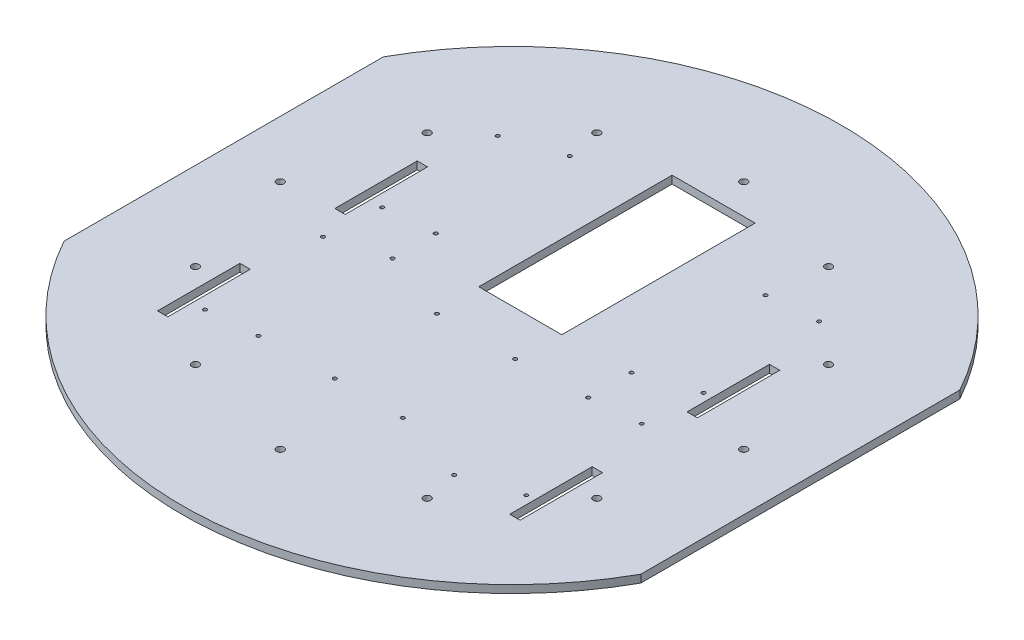
SolidWorks part; units mm, degrees
ref_plane "Front Plane" through (0, 0, 0) normal (0, 0, 1) x (1, 0, 0)
ref_plane "Top Plane" through (0, 0, 0) normal (0, 1, 0) x (1, 0, 0)
ref_plane "Right Plane" through (0, 0, 0) normal (1, 0, 0) x (0, 0, -1)
sketch "Sketch1" plane through (0, 0, 0) normal (0, 1, 0) x (1, 0, 0)
  line L0 (177.8, 98.3738) -> (177.8, -98.3738)
  line L1 (-177.8, 98.3738) -> (-177.8, -98.3738)
  line L2 (0, 0) -> (0, -203.2) construction
  arc A0 (-177.8, -98.3738) -> (177.8, -98.3738) centre (0, 0) ccw
  arc A1 (177.8, 98.3738) -> (-177.8, 98.3738) centre (0, 0) ccw
  dimension "D1" = 406.4
  dimension "D2" = 355.6
extrude "Boss-Extrude1" add sketch "Sketch1" along normal blind 4.7625
sketch "Sketch2" plane through (0, 4.7625, 0) normal (0, 1, 0) x (1, 0, 0)
  line L0 (174.55, -94.8) -> (174.55, -65.2) construction
  line L1 (174.55, 65.2) -> (174.55, 94.8) construction
  line L2 (177.8, -98.3738) -> (177.8, 98.3738) construction
  line L3 (174.55, -80) -> (201.8, -80) construction
  line L4 (201.8, -80) -> (201.8, -130) construction
  point P4 (174.55, 80)
  point P5 (174.55, -80)
  dimension "D1" = 14.8
  dimension "D2" = 14.8
  dimension "D3" = 3.25
  dimension "D4" = 80
  dimension "D5" = 50
  dimension "D6" = 24
  dimension "D7" = 80
sketch "Sketch5" plane through (0, 4.7625, 0) normal (0, 1, 0) x (1, 0, 0)
  circle A0 centre (0, 0) radius 142.875 construction
  point P3 (0, -142.875)
  dimension "D1" = 285.75
hole_wizard "#8 Clearance Hole1" positions "Sketch6" profile "Sketch7" hole size "#8" standard "ANSI Inch" end condition through all
sketch "Sketch6" plane through (0, 4.7625, 0) normal (0, 1, 0) x (1, 0, 0)
  point P0 (0, -142.875)
sketch "Sketch7" plane through (0, 4.7625, 142.875) normal (1, 0, 0) x (0, 0, 1)
  line L0 (0, 0) -> (0, 4.7625)
  line L1 (0, 4.7625) -> (2.2479, 4.7625)
  line L2 (2.2479, 4.7625) -> (2.2479, 0)
  line L5 (2.2479, 0) -> (0, 0)
  line L11 (0, -6.35) -> (0, 107.95) construction
  dimension "Thru Hole Dia." = 4.4958
  dimension "Thru Hole Depth" = 4.7625
pattern_circular "CirPattern1" count 12 over 360 about axis through (0, 0, 0) along (0, 1, 0) of "#8 Clearance Hole1"
hole_wizard "#4-40 Tapped Hole1" positions "Sketch8" profile "Sketch9" tap size "#4-40" standard "ANSI Inch" end condition through all
sketch "Sketch8" plane through (0, 4.7625, 0) normal (0, 1, 0) x (1, 0, 0)
  point P0 (-100.33, 91.5416)
  point P3 (-67.31, 102.9716)
  point P6 (-67.31, 20.32)
  point P9 (-97.79, 17.78)
  point P12 (-100.2962, -16.1869)
  point P14 (-67.31, -6.35)
  point P17 (-67.31, -89.0016)
  point P20 (-97.79, -91.5416)
  point P23 (67.31, -102.9716)
  point P26 (100.33, -91.5416)
  point P29 (97.79, -17.78)
  point P32 (67.31, -20.32)
  point P35 (67.31, 6.35)
  point P38 (100.33, 17.78)
  point P41 (97.79, 91.5416)
  point P44 (67.31, 89.0016)
  point P47 (24.13, -22.225)
  point P50 (-24.13, -22.225)
  point P53 (-20.955, -88.265)
  point P56 (20.955, -88.265)
sketch "Sketch9" plane through (-100.33, 4.7625, -91.5416) normal (1, 0, 0) x (0, 0, 1)
  line L0 (0, 0) -> (0, 4.7625)
  line L1 (0, 4.7625) -> (1.1303, 4.7625)
  line L2 (1.1303, 4.7625) -> (1.1303, 0)
  line L5 (1.1303, 0) -> (0, 0)
  line L11 (0, -6.35) -> (0, 107.95) construction
  dimension "Thread Major Dia." = 2.2606
  dimension "Thru Tap Drill Depth" = 4.7625
sketch "Sketch11" plane through (0, 4.7625, 0) normal (0, 1, 0) x (1, 0, 0)
  line L0 (-25.5946, 124.2998) -> (25.5946, 124.2998)
  line L2 (-25.5946, 124.2998) -> (-25.5946, 5.0952)
  line L3 (-25.5946, 5.0952) -> (25.5946, 5.0952)
  line L4 (25.5946, 124.2998) -> (25.5946, 5.0952)
  point P0 (0, 69.7927)
extrude "Cut-Extrude1" cut sketch "Sketch11" against normal up to next
sketch "Sketch12" plane through (0, 4.7625, 0) normal (0, 1, 0) x (1, 0, 0)
  line L5 (-105.41, 106.7816) -> (-105.41, 2.54) construction
  line L18 (-105.41, 2.54) -> (-111.76, 2.54)
  line L19 (-105.41, 2.54) -> (-105.41, 53.34)
  line L20 (-105.41, 53.34) -> (-111.76, 53.34)
  line L21 (-111.76, 2.54) -> (-111.76, 53.34)
  line L22 (-105.41, 2.54) -> (-63.5, 2.54) construction
  line L24 (-105.41, -106.7816) -> (-111.76, -106.7816)
  line L25 (-105.41, -106.7816) -> (-105.41, -55.9816)
  line L26 (-105.41, -55.9816) -> (-111.76, -55.9816)
  line L27 (-111.76, -106.7816) -> (-111.76, -55.9816)
  line L37 (105.41, 2.54) -> (111.76, 2.54)
  line L38 (105.41, 2.54) -> (105.41, 53.34)
  line L39 (105.41, 53.34) -> (111.76, 53.34)
  line L40 (111.76, 2.54) -> (111.76, 53.34)
  line L41 (105.41, -106.7816) -> (111.76, -106.7816)
  line L42 (105.41, -106.7816) -> (105.41, -55.9816)
  line L43 (105.41, -55.9816) -> (111.76, -55.9816)
  line L44 (111.76, -106.7816) -> (111.76, -55.9816)
  dimension "D1" = 6.35
  dimension "D2" = 50.8
extrude "Cut-Extrude2" cut sketch "Sketch12" against normal up to next
